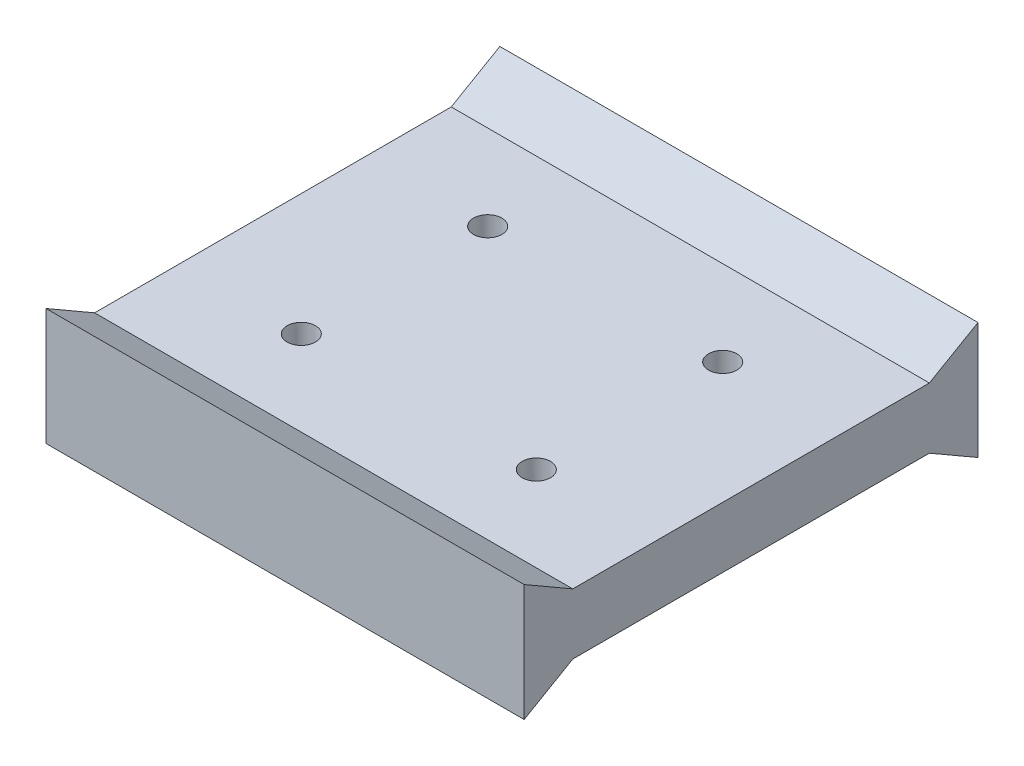
SolidWorks part; units mm, degrees
ref_plane "Front Plane" through (0, 0, 0) normal (0, 0, 1) x (1, 0, 0)
ref_plane "Top Plane" through (0, 0, 0) normal (0, 1, 0) x (1, 0, 0)
ref_plane "Right Plane" through (0, 0, 0) normal (1, 0, 0) x (0, 0, -1)
sketch "Sketch1" plane through (0, 0, 0) normal (0, 1, 0) x (1, 0, 0)
  line L0 (29.5, 44) -> (29.5, 0) construction
  line L1 (0, 0) -> (59, 0)
  line L2 (0, 0) -> (0, 44)
  line L3 (0, 44) -> (59, 44)
  line L4 (59, 0) -> (59, 44)
  line L5 (0, 22) -> (59, 22) construction
  circle A0 centre (15, 10.5) radius 1.75
  circle A1 centre (44, 10.5) radius 1.75
  circle A2 centre (15, 33.5) radius 1.75
  circle A3 centre (44, 33.5) radius 1.75
  dimension "D5" = 3.5
  dimension "D1" = 44
  dimension "D2" = 59
  dimension "D3" = 15
  dimension "D4" = 10.5
extrude "Boss-Extrude1" add sketch "Sketch1" along normal blind 7.5
sketch "Sketch3" plane through (59, 0, 0) normal (1, 0, 0) x (0, 0, -1)
  line L0 (0, 7.5) -> (-6, 10.9641)
  line L1 (-6, 10.9641) -> (-6, -3.4641)
  line L2 (-6, -3.4641) -> (0, 0)
  line L3 (0, 7.5) -> (44, 7.5) construction
  line L4 (0, 0) -> (44, 0) construction
  line L5 (0, 7.5) -> (0, 0) construction
  line L6 (0, 7.5) -> (0, 0)
  line L7 (22, 7.5) -> (22, 0) construction
  line L8 (44, 7.5) -> (50, 10.9641)
  line L9 (50, 10.9641) -> (50, -3.4641)
  line L10 (50, -3.4641) -> (44, 0)
  line L11 (44, 7.5) -> (44, 0)
  dimension "D1" = 30
  dimension "D2" = 30
  dimension "D3" = 6
extrude "Boss-Extrude2" add sketch "Sketch3" against normal up to surface (59 mm away) up to face at (0, 3.75, -22)
